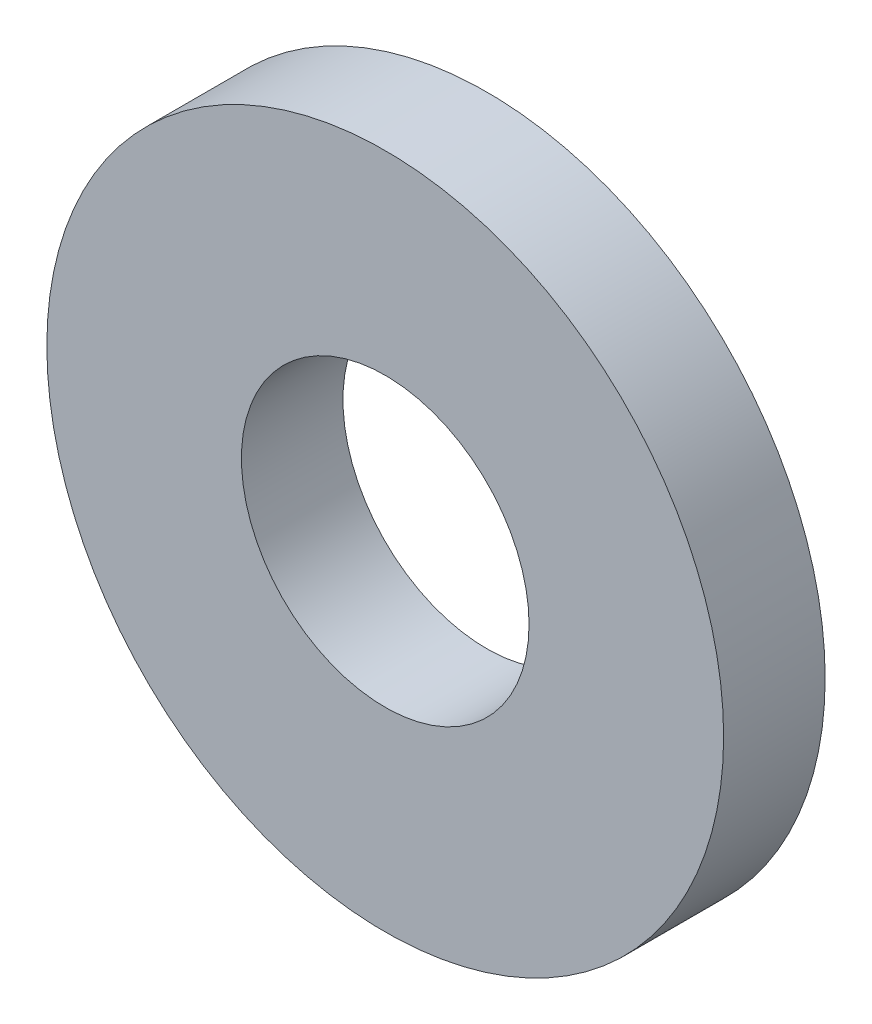
SolidWorks part; units mm, degrees
ref_plane "Alzado" through (0, 0, 0) normal (0, 0, 1) x (1, 0, 0)
ref_plane "Planta" through (0, 0, 0) normal (0, 1, 0) x (1, 0, 0)
ref_plane "Vista lateral" through (0, 0, 0) normal (1, 0, 0) x (0, 0, -1)
sketch "Croquis1" plane through (0, 0, 0) normal (0, 0, 1) x (1, 0, 0)
  circle A0 centre (0, 0) radius 10
  circle A1 centre (0, 0) radius 4.25
  dimension "D1" = 20
  dimension "D2" = 8.5
extrude "Saliente-Extruir1" add sketch "Croquis1" along normal blind 3
